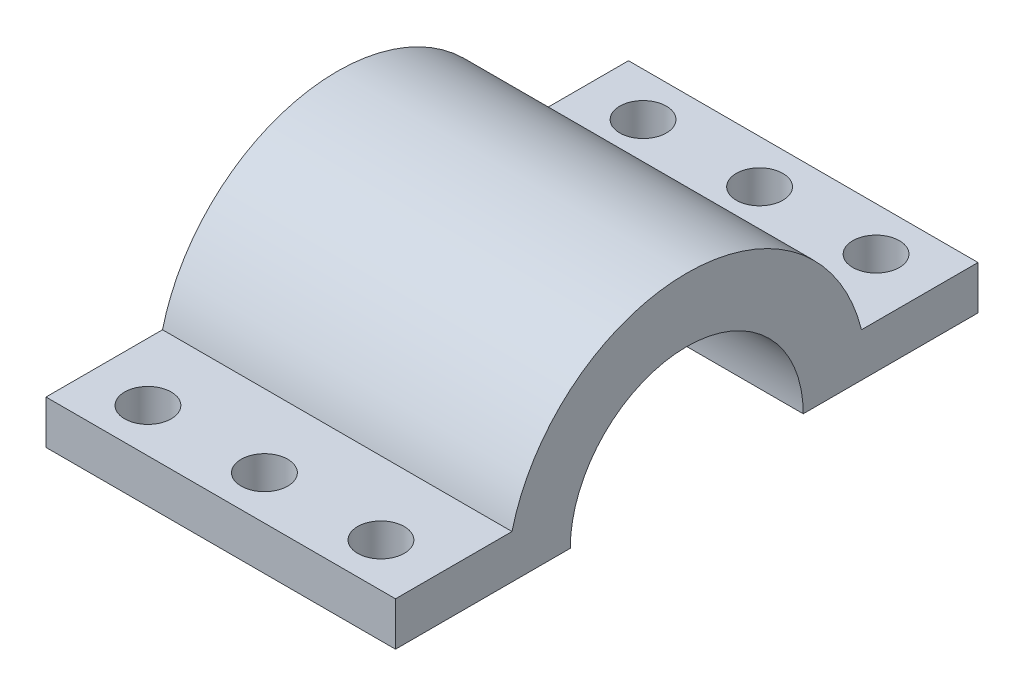
SolidWorks part; units mm, degrees
ref_plane "前视基准面" through (0, 0, 0) normal (0, 0, 1) x (1, 0, 0)
ref_plane "上视基准面" through (0, 0, 0) normal (0, 1, 0) x (1, 0, 0)
ref_plane "右视基准面" through (0, 0, 0) normal (1, 0, 0) x (0, 0, -1)
sketch "草图1" plane through (0, 0, 0) normal (0, 1, 0) x (1, 0, 0)
  line L0 (0, 0) -> (0, 16)
  line L1 (0, 0) -> (16, 0)
  line L2 (0, 16) -> (16, 16)
  line L3 (16, 0) -> (16, 16)
  line L6 (-4, 16) -> (-4, 20)
  line L7 (-4, 20) -> (0, 20)
  line L9 (20, -4) -> (20, 0)
  line L10 (16, -4) -> (20, -4)
  line L13 (-4, 20) -> (20, 20)
  line L14 (-4, 20) -> (-4, -4)
  line L15 (20, 20) -> (20, -4)
  line L16 (-4, -4) -> (20, -4)
extrude "凸台-拉伸1" add sketch "草图1" against normal blind 20 contours L14 L16 L10 L9 L15 L13 L7 L6 L3 L1 L0 L2
sketch "草图2" plane through (0, -20, 0) normal (0, -1, 0) x (1, 0, 0)
  line L4 (20, 4) -> (20, -20)
  line L5 (20, -20) -> (-4, -20)
  line L6 (-4, -20) -> (-4, 4)
  line L7 (-4, 4) -> (20, 4)
extrude "凸台-拉伸4" add sketch "草图2" along normal blind 10
sketch "草图3" plane through (-4, 0, 0) normal (-1, 0, 0) x (0, 0, 1)
  line L0 (4, -30) -> (-20, -30)
  line L1 (8, -38) -> (12, -38)
  line L2 (-24, -38) -> (-16, -38)
  line L3 (8, -38) -> (8, -35)
  line L4 (8, -35) -> (4, -35)
  line L5 (4, -35) -> (4, -30)
  line L6 (-24, -35) -> (-20, -35)
  line L7 (-24, -38) -> (-24, -35)
  line L8 (-20, -35) -> (-20, -30)
  line L9 (0, -38) -> (8, -38)
  line L10 (12, -38) -> (12, -35)
  line L11 (12, -35) -> (8, -35)
  line L12 (-24, -38) -> (-28, -38)
  line L13 (-28, -38) -> (-28, -35)
  line L14 (-28, -35) -> (-24, -35)
  arc A0 (0, -38) -> (-16, -38) centre (-8, -38) ccw
  line M5 (-20, -30) -> (4, -30)
extrude "凸台-拉伸6" add sketch "草图3" against normal blind 24 contours L10 L11 L3 L1 | A0 L9 L3 L4 L5 L0 | A0 L8 L6 L7 L2 M5 | L14 L13 L12 L7
sketch "草图5" plane through (0, -38, 0) normal (0, -1, 0) x (1, 0, 0)
  circle A0 centre (8, 9) radius 1.6
  circle A1 centre (16, 9) radius 1.6
  circle A2 centre (0, 9) radius 1.6
  circle A3 centre (0, -25) radius 1.6
  circle A4 centre (8, -25) radius 1.6
  circle A5 centre (16, -25) radius 1.6
extrude "切除-拉伸1" cut sketch "草图5" against normal blind 24
sketch "草图6" plane through (-4, 0, 0) normal (-1, 0, 0) x (0, 0, 1)
  line L0 (-20, -35) -> (-20, 0) construction
  line L1 (-20, -35) -> (-20, 0)
  line L2 (-20, 0) -> (4, 0)
  line L3 (4, 0) -> (4, -35)
  arc A0 (4, -35) -> (-20, -35) centre (-8, -38) ccw
extrude "切除-拉伸2" cut sketch "草图6" against normal blind 24
